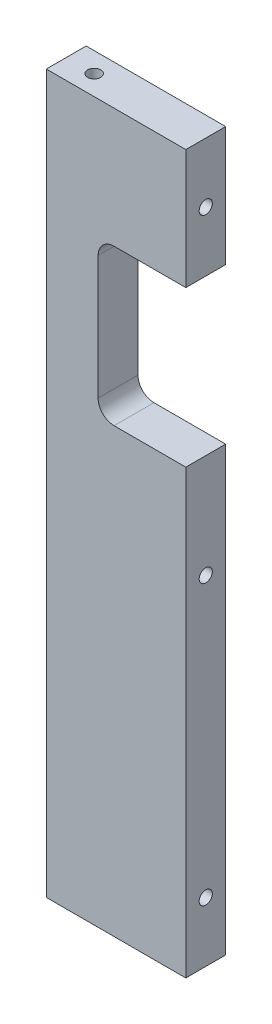
SolidWorks part; units mm, degrees
ref_plane "Спереди" through (0, 0, 0) normal (0, 0, 1) x (1, 0, 0)
ref_plane "Сверху" through (0, 0, 0) normal (0, 1, 0) x (1, 0, 0)
ref_plane "Справа" through (0, 0, 0) normal (1, 0, 0) x (0, 0, -1)
sketch "Эскиз1" plane through (0, 0, 0) normal (0, 0, 1) x (1, 0, 0)
  line L1 (-28.2047, 68.755) -> (6.7953, 68.755)
  line L2 (-28.2047, 68.755) -> (-28.2047, -111.245)
  line L3 (-28.2047, -111.245) -> (6.7953, -111.245)
  line L4 (6.7953, 68.755) -> (6.7953, -111.245)
  dimension "D1" = 180
  dimension "D2" = 35
extrude "Бобышка-Вытянуть1" add sketch "Эскиз1" along normal blind 10
sketch "Эскиз2" plane through (0, 0, 0) normal (0, 0, -1) x (-1, 0, 0)
  line L0 (-6.7953, -111.245) -> (-6.7953, 68.755) construction
  line L1 (-6.7953, 38.755) -> (15.2047, 38.755)
  line L2 (-6.7953, 38.755) -> (-6.7953, -0.245)
  line L3 (-6.7953, -0.245) -> (15.2047, -0.245)
  line L4 (15.2047, 38.755) -> (15.2047, -0.245)
  line L5 (-6.7953, 68.755) -> (28.2047, 68.755) construction
  dimension "D1" = 22
  dimension "D2" = 30
  dimension "D3" = 39
extrude "Вырез-Вытянуть1" cut sketch "Эскиз2" against normal blind 39
fillet "Скругление1" radius 4 2 edges at (-15.2047, 38.755, 5) (-15.2047, -0.245, 5)
sketch "Эскиз3" plane through (-28.2047, 0, 0) normal (-1, 0, 0) x (0, 0, 1)
  circle A0 centre (5, 38.6518) radius 1.65
  circle A1 centre (5, -21.3482) radius 1.65
  circle A2 centre (5, -81.3482) radius 1.65
  dimension "D1" = 3.3
  dimension "D2" = 3.3
  dimension "D3" = 3.3
extrude "Вырез-Вытянуть2" cut sketch "Эскиз3" against normal blind 15
sketch "Эскиз5" plane through (6.7953, 0, 0) normal (1, 0, 0) x (0, 0, -1)
  circle A0 centre (-5, 53.755) radius 1.65
  circle A1 centre (-5, -26.245) radius 1.65
  circle A2 centre (-5, -96.245) radius 1.65
  dimension "D1" = 3.3
  dimension "D2" = 3.3
  dimension "D3" = 3.3
extrude "Вырез-Вытянуть3" cut sketch "Эскиз5" against normal blind 15
sketch "Эскиз6" plane through (0, -111.245, 0) normal (0, -1, 0) x (1, 0, 0)
  line L0 (-28.2047, 5) -> (6.7953, 5) construction
  line L1 (-28.2047, 10) -> (-28.2047, 0) construction
  line L2 (6.7953, 10) -> (6.7953, 0) construction
  circle A0 centre (-22.2047, 5) radius 1.1395
  circle A1 centre (-3.2047, 5) radius 1.2079
  dimension "D1" = 10
  dimension "D2" = 6
extrude "Вырез-Вытянуть4" cut sketch "Эскиз6" against normal blind 12
sketch "Эскиз7" plane through (0, 68.755, 0) normal (0, 1, 0) x (1, 0, 0)
  circle A0 centre (-21.2047, -5) radius 1.65
  dimension "D1" = 3.3
extrude "Вырез-Вытянуть5" cut sketch "Эскиз7" against normal blind 12
